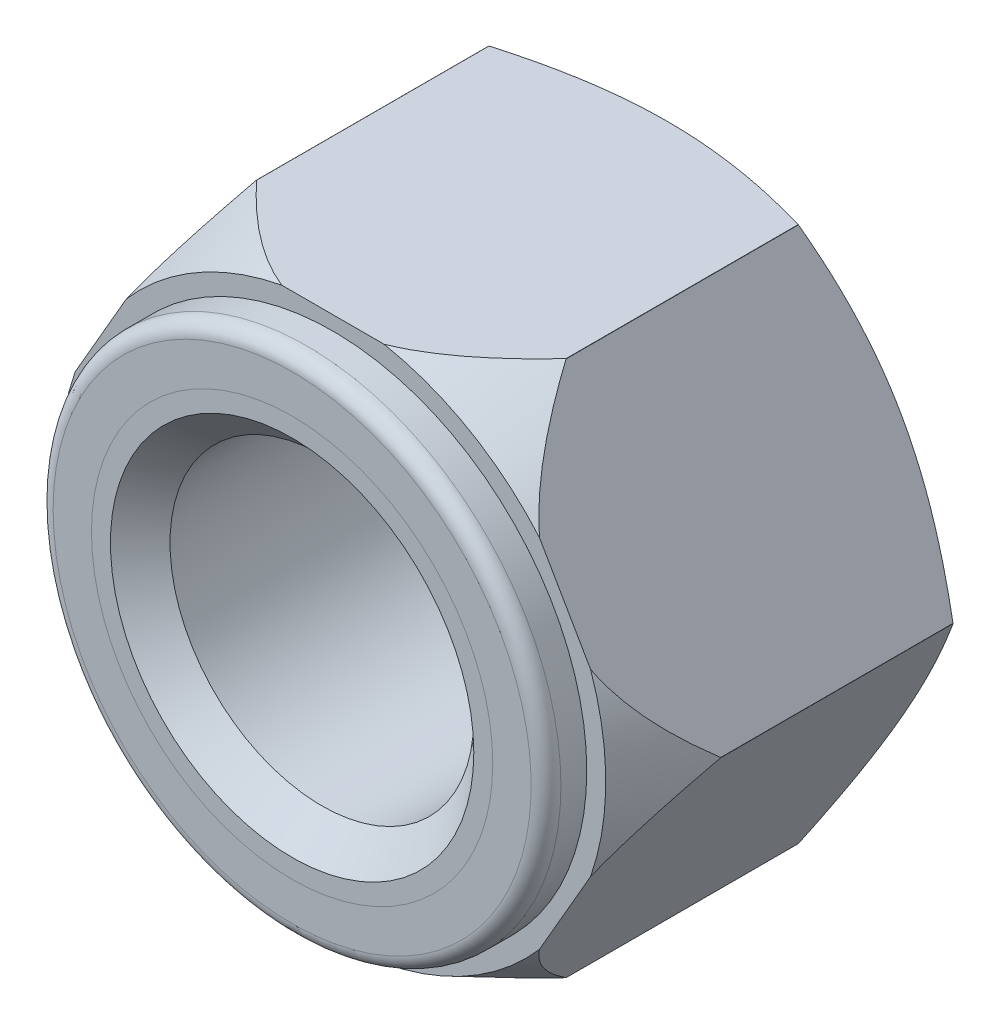
SolidWorks part; units mm, degrees
ref_plane "Front Plane" through (0, 0, 0) normal (0, 0, 1) x (1, 0, 0)
ref_plane "Top Plane" through (0, 0, 0) normal (0, 1, 0) x (1, 0, 0)
ref_plane "Right Plane" through (0, 0, 0) normal (1, 0, 0) x (0, 0, -1)
sketch "Sketch1" plane through (0, 0, 0) normal (1, 0, 0) x (0, 0, -1)
  line L0 (0, 0) -> (71.6388, 0) construction
  line L1 (13.3, 7.7919) -> (13.3, 6.1)
  line L2 (11.8, 10.39) -> (4, 10.39)
  line L3 (4, 10.39) -> (1.3676, 9.1625)
  line L4 (0, 8.5248) -> (0, 6.1)
  line L5 (11.8, 10.39) -> (13.3, 7.7919)
  line L6 (0, 6.1) -> (1, 5.1)
  line L7 (1, 5.1) -> (12.3, 5.1)
  line L8 (12.3, 5.1) -> (13.3, 6.1)
  line L9 (0, 8.5248) -> (1.3676, 8.5248)
  line L10 (1.3676, 8.5248) -> (1.3676, 9.1625)
  dimension "D3" = 25
  dimension "D4" = 60
  dimension "D6" = 45
  dimension "D8" = 1
  dimension "DrillHole" = 10.2
  dimension "D1" = 1.5
  dimension "NutHeight" = 13.3
  dimension "IntChamfer" = 1
  dimension "DCROSS" = 20.78
  dimension "Taperheight" = 4
  dimension "D2" = 1.3676
revolve "Revolve1" add sketch "Sketch1" angle 360 about L0
cosmetic thread "Cosmetic Thread1" parameters "M"=12
sketch "Sketch2" plane through (0, 0, 0) normal (0, 0, 1) x (1, 0, 0)
  line L1 (10.3923, 0) -> (5.1962, 9)
  line L2 (5.1962, 9) -> (-5.1962, 9)
  line L3 (-5.1962, 9) -> (-10.3923, 0)
  line L4 (-10.3923, 0) -> (-5.1962, -9)
  line L5 (-5.1962, -9) -> (5.1962, -9)
  line L6 (5.1962, -9) -> (10.3923, 0)
  circle A0 centre (0, 0) radius 9 construction
  dimension "Flat" = 18
extrude "Cut-Extrude1" cut sketch "Sketch2" against normal up to next flip side to cut
fillet "Fillet1" radius 0.5 1 edges at (8.5248, 0, 0)
sketch "Sketch3" plane through (0, 0, 0) normal (0, 0, 1) x (1, 0, 0)
  circle A0 centre (0, 0) radius 6.7368
  circle A1 centre (0, 0) radius 6.1 construction
  dimension "D1" = 0.6368
split line "Split Line1"
equation "\"D8@Sketch1\" = \"IntChamfer@Sketch1\""
